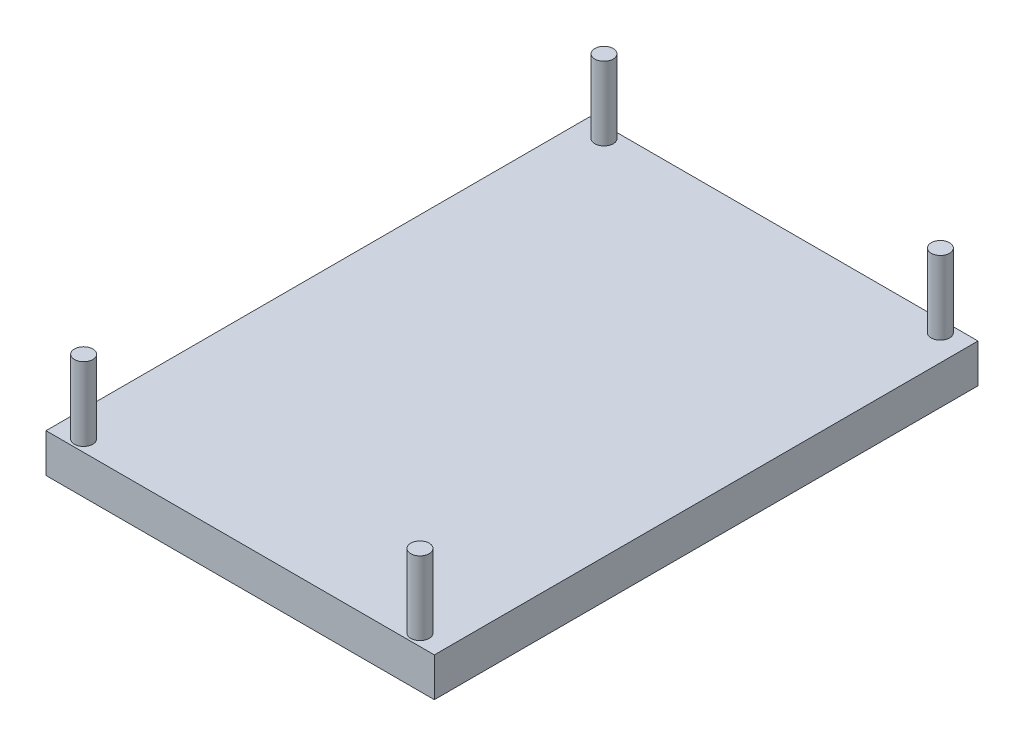
SolidWorks part; units mm, degrees
ref_plane "Front Plane" through (0, 0, 0) normal (0, 0, 1) x (1, 0, 0)
ref_plane "Top Plane" through (0, 0, 0) normal (0, 1, 0) x (1, 0, 0)
ref_plane "Right Plane" through (0, 0, 0) normal (1, 0, 0) x (0, 0, -1)
sketch "Sketch1" plane through (0, 0, 0) normal (0, 1, 0) x (1, 0, 0)
  line L1 (-31.75, -44.45) -> (31.75, -44.45)
  line L2 (-31.75, -44.45) -> (-31.75, 44.45)
  line L3 (-31.75, 44.45) -> (31.75, 44.45)
  line L4 (31.75, -44.45) -> (31.75, 44.45)
  line L5 (-31.75, -44.45) -> (31.75, 44.45) construction
  line L6 (-31.75, 44.45) -> (31.75, -44.45) construction
  point P0 (0, 0)
  dimension "D1" = 63.5
  dimension "D2" = 88.9
extrude "Boss-Extrude1" add sketch "Sketch1" along normal blind 6.35
sketch "Sketch2" plane through (0, 6.35, 0) normal (0, 1, 0) x (1, 0, 0)
  line L1 (-27.5, -42.5477) -> (27.5, -42.5477) construction
  line L2 (-27.5, -42.5477) -> (-27.5, 42.5477) construction
  line L3 (-27.5, 42.5477) -> (27.5, 42.5477) construction
  line L4 (27.5, -42.5477) -> (27.5, 42.5477) construction
  line L5 (-27.5, -42.5477) -> (27.5, 42.5477) construction
  line L6 (-27.5, 42.5477) -> (27.5, -42.5477) construction
  circle A0 centre (-27.5, 42.5477) radius 1.5
  circle A1 centre (27.5, 42.5477) radius 1.5
  circle A2 centre (27.5, -42.5477) radius 1.5
  circle A3 centre (-27.5, -42.5477) radius 1.5
  point P0 (0, 0)
  dimension "D1" = 3
  dimension "D2" = 55
  dimension "D3" = 85.0953
extrude "Boss-Extrude2" add sketch "Sketch2" along normal blind 12
